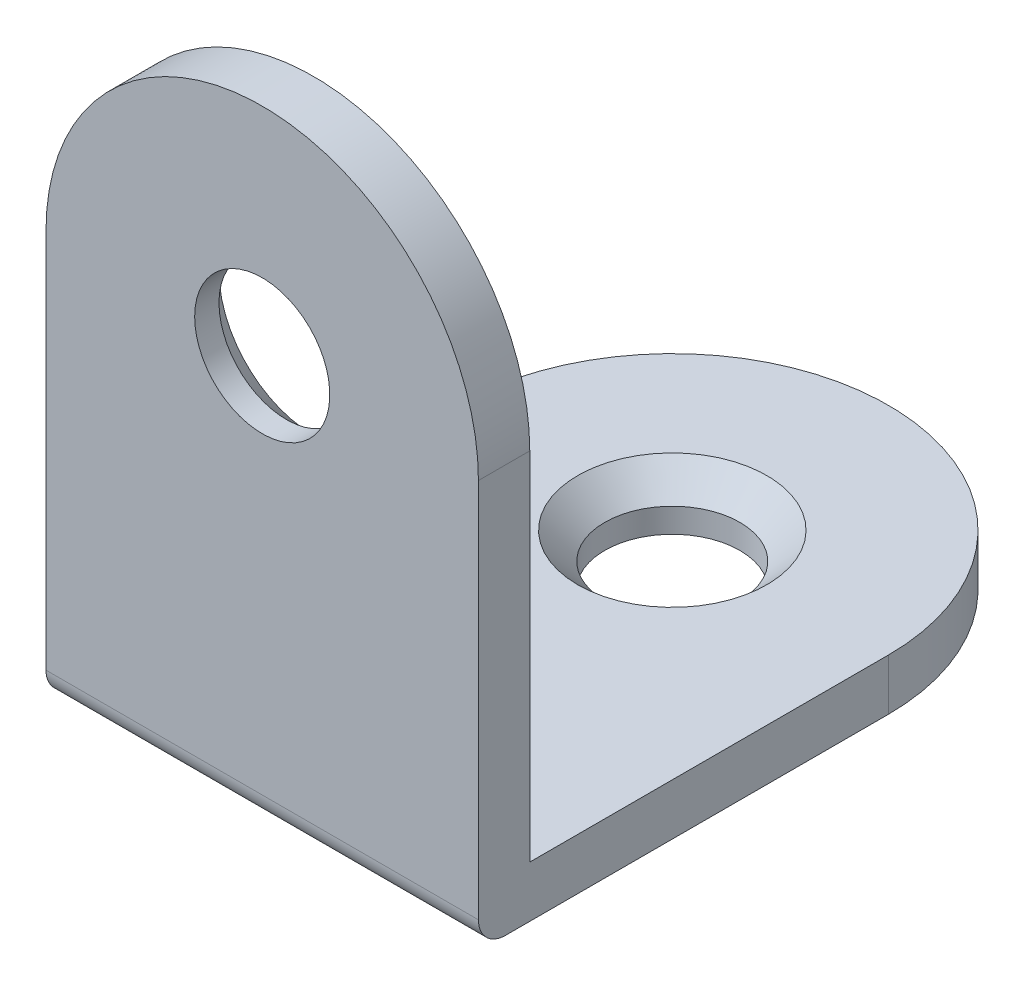
SolidWorks part; units mm, degrees
ref_plane "前视基准面" through (0, 0, 0) normal (0, 0, 1) x (1, 0, 0)
ref_plane "上视基准面" through (0, 0, 0) normal (0, 1, 0) x (1, 0, 0)
ref_plane "右视基准面" through (0, 0, 0) normal (1, 0, 0) x (0, 0, -1)
other "Configuration Table"
sketch "草图1" plane through (0, 0, 0) normal (0, 0, 1) x (1, 0, 0)
  line L0 (0, 0) -> (16, 0)
  line L1 (16, 0) -> (16, 15.0763)
  line L2 (16, 23.0763) -> (0, 23.0763) construction
  line L3 (0, 15.0763) -> (0, -1.6587)
  line L4 (0, 7.0763) -> (16, 7.0763) construction
  line L5 (0, 23.0763) -> (16, 7.0763) construction
  line L6 (16, 23.0763) -> (0, 7.0763) construction
  arc A0 (16, 15.0763) -> (0, 15.0763) centre (8, 15.0763) ccw
  circle A1 centre (8, 15.0763) radius 2.5
  point P12 (0, 0)
  dimension "D1" = 16
extrude "凸台-拉伸1" add sketch "草图1" along normal blind 1.9 contours L1 A0 L3 L0 A1
sketch "草图3" plane through (0, 0, 0) normal (0, 1, 0) x (1, 0, 0)
  line L0 (0, -1.9) -> (16, -1.9)
  line L1 (16, -1.9) -> (16, 13.2727)
  line L2 (16, 21.2727) -> (0, 21.2727) construction
  line L3 (0, 13.2727) -> (0, -1.9)
  line L4 (0, 5.2727) -> (16, 5.2727) construction
  line L5 (0, 21.2727) -> (16, 5.2727) construction
  line L6 (16, 21.2727) -> (0, 5.2727) construction
  line L7 (0, -1.9) -> (16, -1.9) construction
  line L8 (16, 0) -> (0, 0) construction
  line L9 (16, -1.9) -> (16, 0) construction
  arc A0 (16, 13.2727) -> (0, 13.2727) centre (8, 13.2727) ccw
  circle A1 centre (8, 13.2727) radius 2.5
extrude "凸台-拉伸2" add sketch "草图3" along normal blind 1.9
fillet "圆角1" radius 1 1 edges at (8, 0, 1.9)
chamfer "倒角1" distance 1 angle 45 2 edges at (8, 1.9, -10.7727) (10.5, 15.0763, 0)
